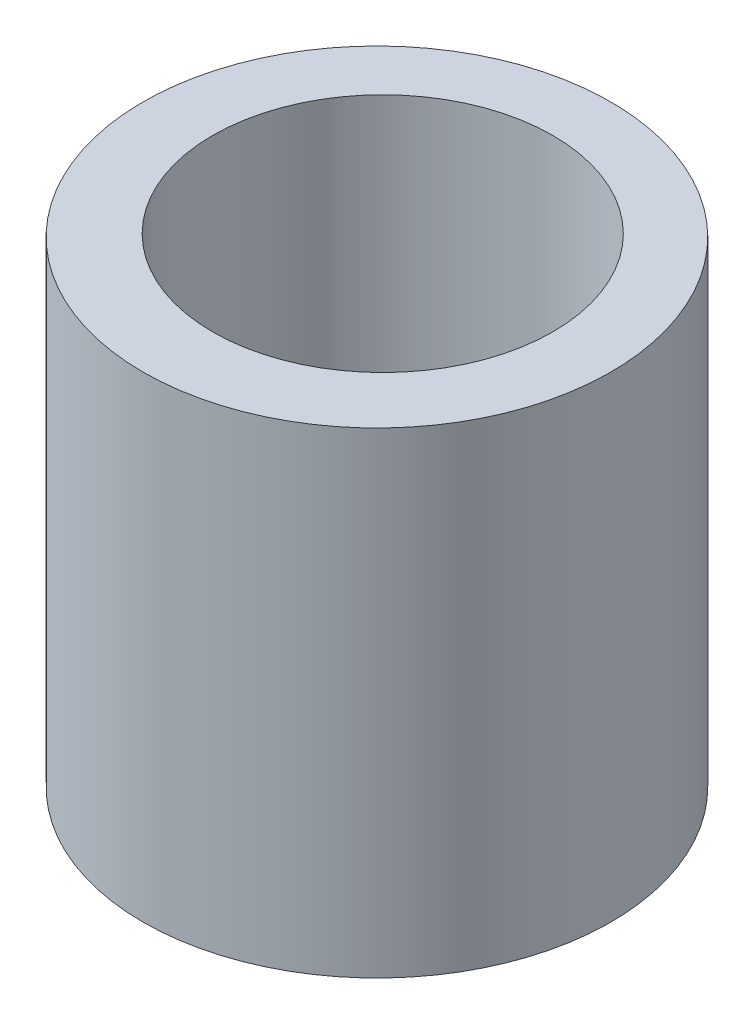
SolidWorks part; units mm, degrees
ref_plane "Front Plane" through (0, 0, 0) normal (0, 0, 1) x (1, 0, 0)
ref_plane "Top Plane" through (0, 0, 0) normal (0, 1, 0) x (1, 0, 0)
ref_plane "Right Plane" through (0, 0, 0) normal (1, 0, 0) x (0, 0, -1)
sketch "Sketch1" plane through (0, 0, 0) normal (0, 1, 0) x (1, 0, 0)
  circle A0 centre (0, 0) radius 5.08
  circle A1 centre (0, -0.1726) radius 6.985
  dimension "D1" = 10.16
  dimension "D2" = 13.97
extrude "Boss-Extrude1" add sketch "Sketch1" along normal blind 14.224
